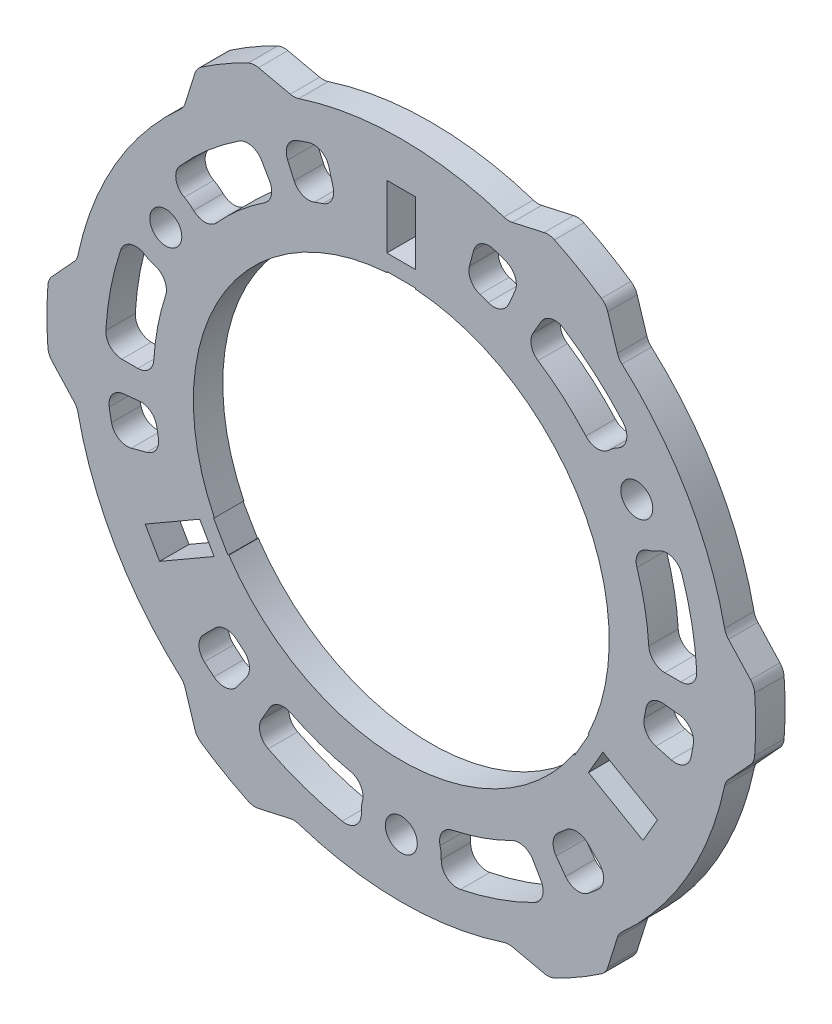
SolidWorks part; units mm, degrees
ref_plane "Front Plane" through (0, 0, 0) normal (0, 0, 1) x (1, 0, 0)
ref_plane "Top Plane" through (0, 0, 0) normal (0, 1, 0) x (1, 0, 0)
ref_plane "Right Plane" through (0, 0, 0) normal (1, 0, 0) x (0, 0, -1)
sketch "Sketch1" plane through (0, 0, 0) normal (0, 0, 1) x (1, 0, 0)
  line L0 (0, 0) -> (0, 50.8) construction
  line L1 (47.9712, -31.0114) -> (50.8422, -26.0386)
  line L2 (2.871, 57.05) -> (-2.871, 57.05)
  line L3 (2.871, 57.05) -> (2.871, 44.55)
  line L4 (2.871, 44.55) -> (-2.871, 44.55)
  line L5 (-2.871, 57.05) -> (-2.871, 44.55)
  line L6 (2.871, 57.05) -> (-2.871, 44.55) construction
  line L7 (2.871, 44.55) -> (-2.871, 57.05) construction
  line L8 (47.9712, -31.0114) -> (37.1459, -24.7614)
  line L9 (37.1459, -24.7614) -> (40.0169, -19.7886)
  line L10 (50.8422, -26.0386) -> (40.0169, -19.7886)
  line L11 (47.9712, -31.0114) -> (40.0169, -19.7886) construction
  line L12 (37.1459, -24.7614) -> (50.8422, -26.0386) construction
  line L13 (-50.8422, -26.0386) -> (-47.9712, -31.0114)
  line L14 (-50.8422, -26.0386) -> (-40.0169, -19.7886)
  line L15 (-40.0169, -19.7886) -> (-37.1459, -24.7614)
  line L16 (-47.9712, -31.0114) -> (-37.1459, -24.7614)
  line L17 (-50.8422, -26.0386) -> (-37.1459, -24.7614) construction
  line L18 (-40.0169, -19.7886) -> (-47.9712, -31.0114) construction
  line L19 (-2.871, 41.375) -> (2.871, 41.375)
  line L20 (-2.871, 41.175) -> (-2.871, 41.375)
  line L21 (2.871, 41.175) -> (2.871, 41.375)
  line L22 (34.2231, -23.0739) -> (34.3963, -23.1739)
  line L23 (37.2673, -18.2011) -> (34.3963, -23.1739)
  line L24 (37.0941, -18.1012) -> (37.2673, -18.2011)
  line L25 (-37.0941, -18.1012) -> (-37.2673, -18.2011)
  line L26 (-34.3963, -23.1739) -> (-37.2673, -18.2011)
  line L27 (0, 0) -> (32.5438, 56.3674) construction
  line L28 (-34.2231, -23.0739) -> (-34.3963, -23.1739)
  arc A0 (-2.871, 41.175) -> (-37.0941, -18.1012) centre (0, 0) ccw
  circle A1 centre (0, 0) radius 65.0875
  circle A2 centre (0, 0) radius 50.8 construction
  arc A3 (37.0941, -18.1012) -> (2.871, 41.175) centre (0, 0) ccw
  arc A4 (-34.2231, -23.0739) -> (34.2231, -23.0739) centre (0, 0) ccw
  point P21 (0, 0)
  point P32 (0, 0)
  point P34 (0, 0)
  dimension "D1" = 82.55
  dimension "D2" = 130.175
  dimension "D8" = 3.175
  dimension "D10" = 101.6
  dimension "D3" = 50.8
  dimension "D4" = 12.5
  dimension "D5" = 5.742
  dimension "D7" = 30
  dimension "D6" = 3
  dimension "D9" = 3
extrude "Boss-Extrude1" add sketch "Sketch1" along normal blind 5.842
sketch "Sketch3" plane through (0, 0, 5.842) normal (0, 0, 1) x (1, 0, 0)
  line L0 (0, 0) -> (0, 65.0875) construction
  line L1 (0, 0) -> (-56.3674, 32.5437) construction
  line L2 (-24.6063, 42.6193) -> (-29.3688, 50.8682)
  line L3 (-49.2125, 0) -> (-58.7375, 0)
  line L4 (-41.2731, 26.803) -> (-49.2614, 31.9907)
  line L5 (-43.8487, 22.342) -> (-52.3355, 26.6663)
  line L6 (43.8487, 22.342) -> (52.3355, 26.6663)
  line L7 (41.2731, 26.803) -> (49.2614, 31.9907)
  line L8 (24.6063, 42.6193) -> (29.3688, 50.8682)
  line L9 (49.2125, 0) -> (58.7375, 0)
  line L10 (-2.5756, -49.1451) -> (-3.0741, -58.657)
  line L11 (2.5756, -49.1451) -> (3.0741, -58.657)
  line L12 (24.6062, -42.6193) -> (29.3687, -50.8682)
  line L13 (-24.6063, -42.6193) -> (-29.3688, -50.8682)
  line L14 (-20.0165, 44.9579) -> (-23.8907, 53.6594)
  line L15 (-15.2024, 56.7361) -> (-12.7371, 47.5356)
  line L16 (-56.7361, -15.2024) -> (-47.5356, -12.7371)
  line L17 (-48.9429, -5.1441) -> (-58.4157, -6.1397)
  line L18 (48.9429, -5.1441) -> (58.4157, -6.1397)
  line L19 (56.7361, -15.2024) -> (47.5356, -12.7371)
  line L20 (15.2024, 56.7361) -> (12.7371, 47.5356)
  line L21 (20.0165, 44.9579) -> (23.8907, 53.6594)
  line L22 (-28.9264, -39.8137) -> (-34.525, -47.5196)
  line L23 (-41.5337, -41.5337) -> (-34.7985, -34.7985)
  line L24 (41.5337, -41.5337) -> (34.7985, -34.7985)
  line L25 (28.9264, -39.8137) -> (34.525, -47.5196)
  circle A0 centre (0, 0) radius 65.0875 construction
  arc A1 (-29.3688, 50.8682) -> (-49.2614, 31.9907) centre (0, 0) ccw
  arc A2 (-24.6063, 42.6193) -> (-41.2731, 26.803) centre (0, 0) ccw
  arc A3 (-43.8487, 22.342) -> (-49.2125, 0) centre (0, 0) ccw
  circle A4 centre (0, 0) radius 49.2125 construction
  circle A5 centre (0, 0) radius 58.7375 construction
  arc A6 (-52.3355, 26.6663) -> (-58.7375, 0) centre (0, 0) ccw
  arc A7 (58.7375, 0) -> (52.3355, 26.6663) centre (0, 0) ccw
  arc A8 (49.2614, 31.9907) -> (29.3688, 50.8682) centre (0, 0) ccw
  arc A9 (41.2731, 26.803) -> (24.6063, 42.6193) centre (0, 0) ccw
  arc A10 (49.2125, 0) -> (43.8487, 22.342) centre (0, 0) ccw
  arc A11 (-29.3688, -50.8682) -> (-3.0741, -58.657) centre (0, 0) ccw
  arc A12 (3.0741, -58.657) -> (29.3687, -50.8682) centre (0, 0) ccw
  arc A13 (2.5756, -49.1451) -> (24.6062, -42.6193) centre (0, 0) ccw
  arc A14 (-24.6063, -42.6193) -> (-2.5756, -49.1451) centre (0, 0) ccw
  arc A15 (-24.6063, 42.6193) -> (-41.2731, 26.803) centre (0, 0) ccw
  arc A16 (-29.3688, 50.8682) -> (-49.2614, 31.9907) centre (0, 0) ccw
  arc A17 (-43.8487, 22.342) -> (-49.2125, 0) centre (0, 0) ccw
  arc A18 (-52.3355, 26.6663) -> (-58.7375, 0) centre (0, 0) ccw
  arc A19 (-24.6063, -42.6193) -> (-2.5756, -49.1451) centre (0, 0) ccw
  arc A20 (-29.3688, -50.8682) -> (-3.0741, -58.657) centre (0, 0) ccw
  arc A21 (2.5756, -49.1451) -> (24.6062, -42.6193) centre (0, 0) ccw
  arc A22 (3.0741, -58.657) -> (29.3687, -50.8682) centre (0, 0) ccw
  arc A23 (58.7375, 0) -> (52.3355, 26.6663) centre (0, 0) ccw
  arc A24 (49.2125, 0) -> (43.8487, 22.342) centre (0, 0) ccw
  arc A25 (41.2731, 26.803) -> (24.6063, 42.6193) centre (0, 0) ccw
  arc A26 (49.2614, 31.9907) -> (29.3688, 50.8682) centre (0, 0) ccw
  arc A27 (-12.7371, 47.5356) -> (-20.0165, 44.9579) centre (0, 0) ccw
  arc A28 (-15.2024, 56.7361) -> (-23.8907, 53.6594) centre (0, 0) ccw
  arc A29 (-56.7361, -15.2024) -> (-58.4157, -6.1397) centre (0, 0) cw
  arc A30 (-47.5356, -12.7371) -> (-48.9429, -5.1441) centre (0, 0) cw
  arc A31 (56.7361, -15.2024) -> (58.4157, -6.1397) centre (0, 0) ccw
  arc A32 (47.5356, -12.7371) -> (48.9429, -5.1441) centre (0, 0) ccw
  arc A33 (15.2024, 56.7361) -> (23.8907, 53.6594) centre (0, 0) cw
  arc A34 (12.7371, 47.5356) -> (20.0165, 44.9579) centre (0, 0) cw
  arc A35 (-41.5337, -41.5337) -> (-34.525, -47.5196) centre (0, 0) ccw
  arc A36 (-34.7985, -34.7985) -> (-28.9264, -39.8137) centre (0, 0) ccw
  arc A37 (41.5337, -41.5337) -> (34.525, -47.5196) centre (0, 0) cw
  arc A38 (34.7985, -34.7985) -> (28.9264, -39.8137) centre (0, 0) cw
  point P8 (56.171, 17.1732)
  point P13 (49.2125, 0)
  point P38 (0, 0)
  point P63 (0, 0)
  dimension "D2" = 117.475
  dimension "D1" = 60
  dimension "D4" = 30
  dimension "D5" = 3
  dimension "D7" = 36
  dimension "D8" = 45
  dimension "D3" = 9.525
  dimension "D6" = 3
  dimension "D9" = 3
extrude "Cut-Extrude2" cut sketch "Sketch3" against normal through all contours A2 L2 A1 L4 | L5 A6 L3 A3 | L16 A30 L17 A29 | L15 A28 L14 A27 | L20 A34 L21 A33 | A9 L7 A8 L8 | A10 L9 A7 L6 | A32 L19 A31 L18 | L24 A38 L25 A37 | A13 L11 A12 L12 | A14 L13 A11 L10 | A36 L23 A35 L22
fillet "Fillet1" radius 3.175 48 edges at (-52.3355, 26.6663, 2.921) (-58.4157, -6.1397, 2.921) (-43.8487, 22.342, 2.921) (-48.9429, -5.1441, 2.921) (-58.7375, 0, 2.921) (-56.7361, -15.2024, 2.921) (-47.5356, -12.7371, 2.921) (-49.2125, 0, 2.921) (-41.2731, 26.803, 2.921) (-49.2614, 31.9907, 2.921) (-20.0165, 44.9579, 2.921) (-12.7371, 47.5356, 2.921) (-15.2024, 56.7361, 2.921) (-23.8907, 53.6594, 2.921) (-29.3688, 50.8682, 2.921) (-24.6063, 42.6193, 2.921) (41.5337, -41.5337, 2.921) (34.525, -47.5196, 2.921) (34.7985, -34.7985, 2.921) (28.9264, -39.8137, 2.921) (3.0741, -58.657, 2.921) (2.5756, -49.1451, 2.921) (24.6062, -42.6193, 2.921) (29.3687, -50.8682, 2.921) (-3.0741, -58.657, 2.921) (-2.5756, -49.1451, 2.921) (-29.3688, -50.8682, 2.921) (-24.6063, -42.6193, 2.921) (-28.9264, -39.8137, 2.921) (-41.5337, -41.5337, 2.921) (-34.7985, -34.7985, 2.921) (-34.525, -47.5196, 2.921) (48.9429, -5.1441, 2.921) (58.4157, -6.1397, 2.921) (56.7361, -15.2024, 2.921) (47.5356, -12.7371, 2.921) (58.7375, 0, 2.921) (49.2125, 0, 2.921) (52.3355, 26.6663, 2.921) (43.8487, 22.342, 2.921) (49.2614, 31.9907, 2.921) (41.2731, 26.803, 2.921) (29.3688, 50.8682, 2.921) (23.8907, 53.6594, 2.921) (15.2024, 56.7361, 2.921) (24.6063, 42.6193, 2.921) (12.7371, 47.5356, 2.921) (20.0165, 44.9579, 2.921)
sketch "Sketch4" plane through (0, 0, 5.842) normal (0, 0, 1) x (1, 0, 0)
  circle A0 centre (0, 0) radius 65.0875
  circle A1 centre (0, 0) radius 65.5875
  dimension "D1" = 0.5
extrude "Boss-Extrude2" add sketch "Sketch4" against normal up to surface (5.842 mm away) up to face at (-15.0326, -50.7493, 0)
sketch "Sketch5" plane through (0, 0, 5.842) normal (0, 0, 1) x (1, 0, 0)
  line L0 (0, 0) -> (64.6093, 37.3022) construction
  line L1 (0, 0) -> (0, 44.55) construction
  line L2 (-2.871, 44.55) -> (2.871, 44.55) construction
  circle A0 centre (46.7437, 26.9875) radius 3.175
  circle A1 centre (46.7437, 26.9875) radius 7.9375
  circle A2 centre (0, -53.975) radius 7.9375
  circle A3 centre (0, -53.975) radius 3.175
  circle A4 centre (-46.7437, 26.9875) radius 7.9375
  circle A5 centre (-46.7437, 26.9875) radius 3.175
  point P17 (0, 0)
  dimension "D2" = 6.35
  dimension "D4" = 15.875
  dimension "D1" = 60
  dimension "D3" = 53.975
  dimension "D5" = 3
extrude "Boss-Extrude3" add sketch "Sketch5" against normal up to surface (5.842 mm away) up to face at (-15.0326, -50.7493, 0)
sketch "Sketch6" plane through (0, 0, 5.842) normal (0, 0, 1) x (1, 0, 0)
  circle A0 centre (46.7437, 26.9875) radius 3.175
  circle A1 centre (0, -53.975) radius 3.175
  circle A2 centre (-46.7437, 26.9875) radius 3.175
  point P9 (0, 0)
  dimension "D2" = 53.975
  dimension "D1" = 3
extrude "Cut-Extrude3" cut sketch "Sketch6" against normal through all
fillet "Fillet2" radius 3.175 12 edges at (47.2378, 34.9096, 2.921) (39.2699, 29.6606, 2.921) (45.3217, 19.1784, 2.921) (53.8515, 23.4544, 2.921) (-39.2699, 29.6606, 2.921) (-45.3217, 19.1784, 2.921) (-53.8515, 23.4544, 2.921) (-47.2378, 34.9096, 2.921) (6.0519, -48.839, 2.921) (-6.0519, -48.839, 2.921) (-6.6137, -58.364, 2.921) (6.6137, -58.364, 2.921)
sketch "Sketch7" plane through (0, 0, 5.842) normal (0, 0, 1) x (1, 0, 0)
  line L0 (0, 0) -> (0, 68.7625) construction
  line L1 (0, 0) -> (34.3813, 59.5501) construction
  line L2 (29.4048, 63.9099) -> (21.1746, 62.0754)
  line L3 (40.6452, 57.4203) -> (43.1716, 49.3754)
  line L4 (70.05, 6.4897) -> (64.3462, 12.7)
  line L5 (70.05, -6.4897) -> (64.3462, -12.7)
  line L6 (40.6452, -57.4203) -> (43.1716, -49.3754)
  line L7 (29.4048, -63.9099) -> (21.1746, -62.0754)
  line L8 (-29.4048, -63.9099) -> (-21.1746, -62.0754)
  line L9 (-40.6452, -57.4203) -> (-43.1716, -49.3754)
  line L10 (-70.05, -6.4897) -> (-64.3462, -12.7)
  line L11 (-70.05, 6.4897) -> (-64.3462, 12.7)
  line L12 (-40.6452, 57.4203) -> (-43.1716, 49.3754)
  line L13 (-29.4048, 63.9099) -> (-21.1746, 62.0754)
  arc A0 (43.1716, 49.3754) -> (21.1746, 62.0754) centre (0, 0) ccw
  arc A1 (40.6452, 57.4203) -> (29.4048, 63.9099) centre (0, 0) ccw
  circle A2 centre (0, 0) radius 65.5875 construction
  circle A3 centre (0, 0) radius 70.35 construction
  circle A4 centre (0, 0) radius 65.5875 construction
  arc A5 (64.3462, -12.7) -> (64.3462, 12.7) centre (0, 0) ccw
  arc A6 (70.05, -6.4897) -> (70.05, 6.4897) centre (0, 0) ccw
  arc A7 (21.1746, -62.0754) -> (43.1716, -49.3754) centre (0, 0) ccw
  arc A8 (29.4048, -63.9099) -> (40.6452, -57.4203) centre (0, 0) ccw
  arc A9 (-43.1716, -49.3754) -> (-21.1746, -62.0754) centre (0, 0) ccw
  arc A10 (-40.6452, -57.4203) -> (-29.4048, -63.9099) centre (0, 0) ccw
  arc A11 (-64.3462, 12.7) -> (-64.3462, -12.7) centre (0, 0) ccw
  arc A12 (-70.05, 6.4897) -> (-70.05, -6.4897) centre (0, 0) ccw
  arc A13 (-21.1746, 62.0754) -> (-43.1716, 49.3754) centre (0, 0) ccw
  arc A14 (-29.4048, 63.9099) -> (-40.6452, 57.4203) centre (0, 0) ccw
  point P35 (0, 0)
  dimension "D2" = 30
  dimension "D3" = 6
  dimension "D4" = 12.7
  dimension "D1" = 4.7625
extrude "Boss-Extrude4" add sketch "Sketch7" against normal up to surface (5.842 mm away) up to face at (-52.3172, 10.0368, 0)
fillet "Fillet3" radius 3.175 24 edges at (29.4048, 63.9099, 2.921) (40.6452, 57.4203, 2.921) (43.1716, 49.3754, 2.921) (21.1746, 62.0754, 2.921) (64.3462, 12.7, 2.921) (70.05, 6.4897, 2.921) (70.05, -6.4897, 2.921) (64.3462, -12.7, 2.921) (21.1746, -62.0754, 2.921) (29.4048, -63.9099, 2.921) (40.6452, -57.4203, 2.921) (43.1716, -49.3754, 2.921) (-40.6452, -57.4203, 2.921) (-29.4048, -63.9099, 2.921) (-21.1746, -62.0754, 2.921) (-43.1716, -49.3754, 2.921) (-70.05, 6.4897, 2.921) (-70.05, -6.4897, 2.921) (-64.3462, -12.7, 2.921) (-64.3462, 12.7, 2.921) (-21.1746, 62.0754, 2.921) (-43.1716, 49.3754, 2.921) (-40.6452, 57.4203, 2.921) (-29.4048, 63.9099, 2.921)
